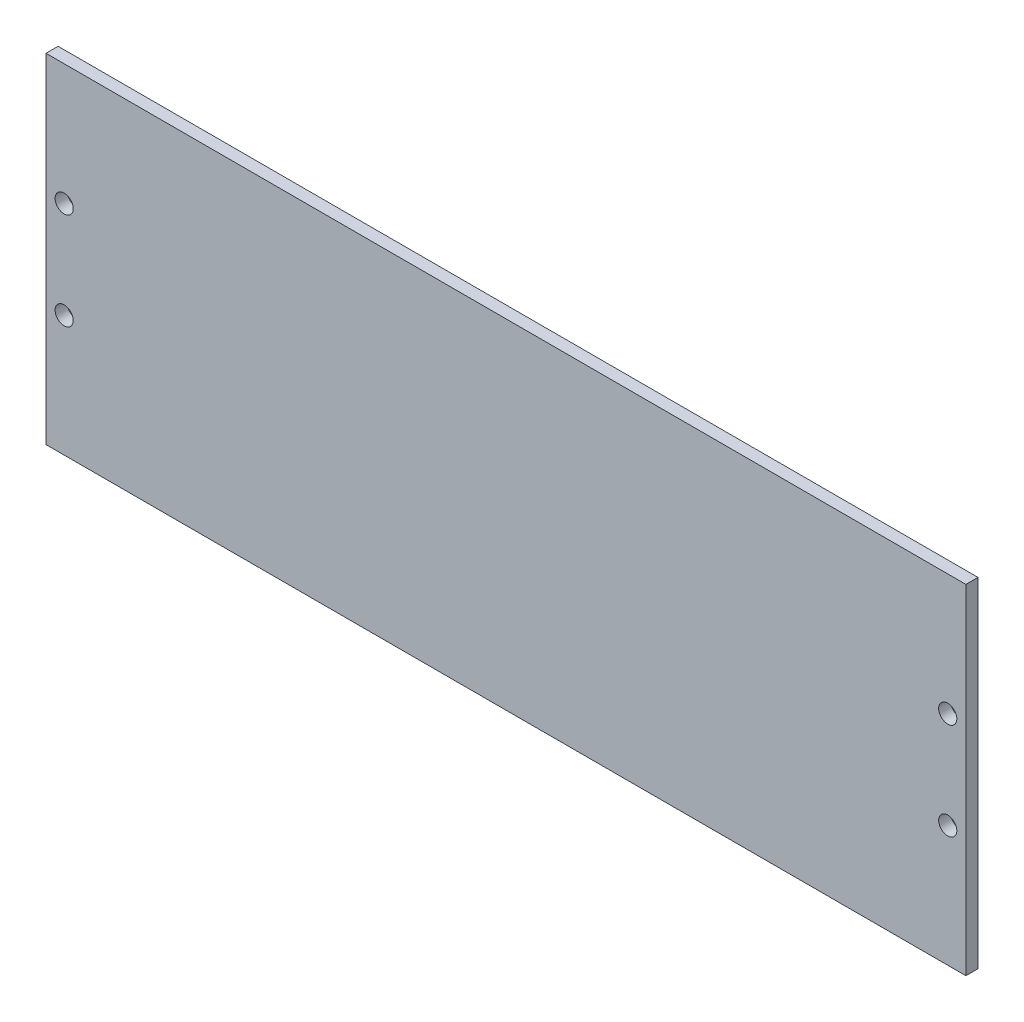
SolidWorks part; units mm, degrees
ref_plane "Plan de face" through (0, 0, 0) normal (0, 0, 1) x (1, 0, 0)
ref_plane "Plan de dessus" through (0, 0, 0) normal (0, 1, 0) x (1, 0, 0)
ref_plane "Plan de droite" through (0, 0, 0) normal (1, 0, 0) x (0, 0, -1)
sketch "Esquisse1" plane through (0, 0, 0) normal (0, 0, 1) x (1, 0, 0)
  line L0 (0, 56) -> (3, 56) construction
  line L1 (0, 0) -> (152, 0)
  line L2 (0, 0) -> (0, 56)
  line L4 (152, 0) -> (152, 56)
  line L5 (3, 56) -> (3, 36) construction
  line L6 (3, 36) -> (3, 20) construction
  line L7 (3, 20) -> (3, 0) construction
  line L8 (152, 56) -> (149, 56) construction
  line L9 (149, 56) -> (149, 36) construction
  line L10 (149, 36) -> (149, 20) construction
  line L11 (149, 20) -> (149, 0) construction
  line L12 (0, 56) -> (152, 56)
  circle A0 centre (3, 36) radius 1.5
  circle A1 centre (3, 20) radius 1.5
  circle A2 centre (149, 20) radius 1.5
  circle A3 centre (149, 36) radius 1.5
  point P17 (0, 0)
extrude "Boss.-Extru.1" add sketch "Esquisse1" along normal blind 2
